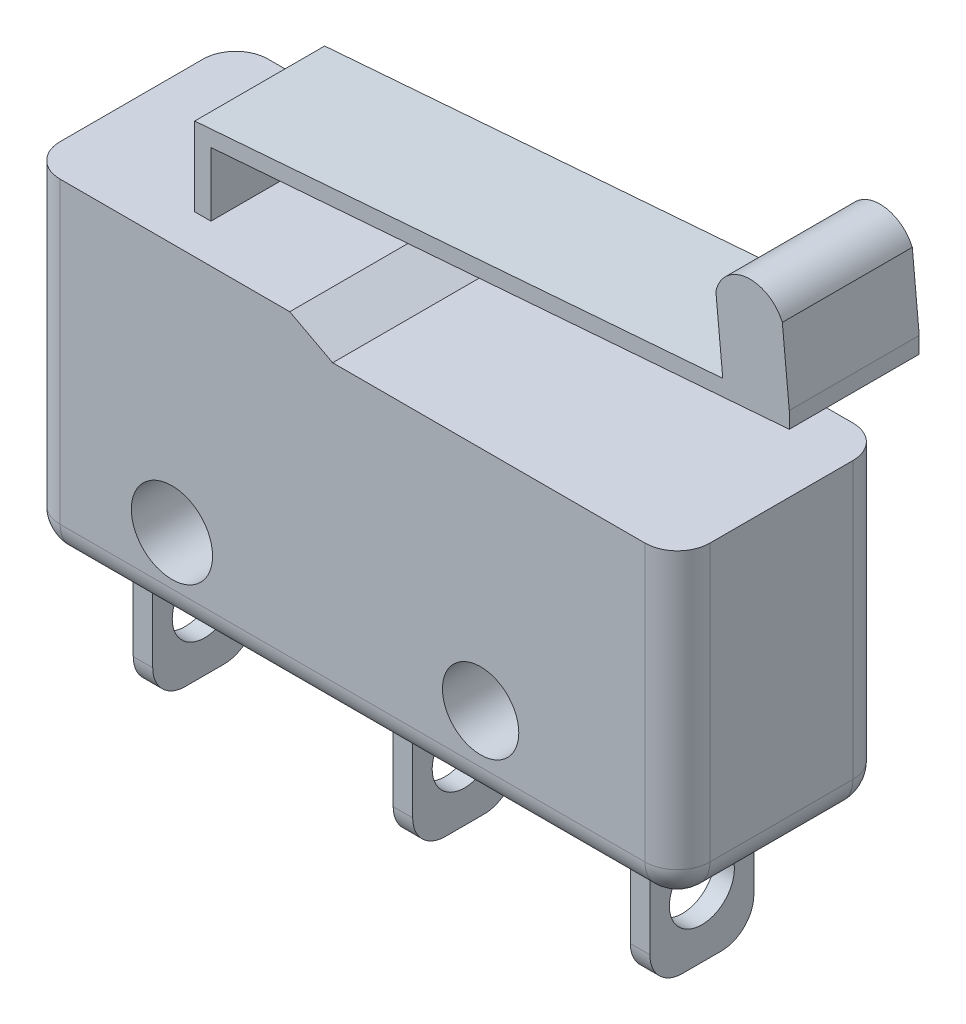
SolidWorks part; units mm, degrees
ref_plane "前视基准面" through (0, 0, 0) normal (0, 0, 1) x (1, 0, 0)
ref_plane "上视基准面" through (0, 0, 0) normal (0, 1, 0) x (1, 0, 0)
ref_plane "右视基准面" through (0, 0, 0) normal (1, 0, 0) x (0, 0, -1)
sketch "草图1" plane through (0, 0, 0) normal (0, 0, 1) x (1, 0, 0)
  line L0 (0, 0) -> (9.5, 0) construction
  line L1 (-4.4408, -2.5) -> (15.5592, -2.5)
  line L2 (15.5592, -2.5) -> (15.5592, 7)
  line L3 (15.5592, 7) -> (4.9467, 7)
  line L4 (4.9467, 7) -> (3.6257, 7.7)
  line L5 (3.6257, 7.7) -> (-4.4408, 7.7)
  line L6 (-4.4408, 7.7) -> (-4.4408, -2.5)
  circle A0 centre (0, 0) radius 1.25
  circle A1 centre (9.5, 0) radius 1.175
  dimension "D2" = 2.5
  dimension "D3" = 2.35
  dimension "D1" = 9.5
  dimension "D4" = 2.5
  dimension "D5" = 20
  dimension "D6" = 9.5
  dimension "D7" = 10.2
extrude "凸台-拉伸1" add sketch "草图1" along normal blind 6.4
sketch "草图3" plane through (0, -2.5, 0) normal (0, -1, 0) x (1, 0, 0)
  line L0 (-4.4408, 6.4) -> (-4.4408, 0) construction
  line L1 (12.5092, 4.8) -> (13.1092, 4.8)
  line L2 (12.5092, 4.8) -> (12.5092, 1.6)
  line L3 (-2.7908, 4.8) -> (-2.1908, 4.8)
  line L4 (-2.7908, 4.8) -> (-2.7908, 1.6)
  line L5 (-2.7908, 1.6) -> (-2.1908, 1.6)
  line L6 (-2.1908, 4.8) -> (-2.1908, 1.6)
  line L7 (5.2092, 4.8) -> (5.8092, 4.8)
  line L8 (5.2092, 4.8) -> (5.2092, 1.6)
  line L9 (5.2092, 1.6) -> (5.8092, 1.6)
  line L10 (5.8092, 4.8) -> (5.8092, 1.6)
  line L11 (12.5092, 1.6) -> (13.1092, 1.6)
  line L12 (13.1092, 4.8) -> (13.1092, 1.6)
  line L13 (-4.4408, 6.4) -> (15.5592, 6.4) construction
  dimension "D1" = 3.2
  dimension "D2" = 0.6
  dimension "D3" = 1.65
  dimension "D4" = 8
  dimension "D5" = 7.3
  dimension "D6" = 1.6
extrude "凸台-拉伸2" add sketch "草图3" along normal blind 4
sketch "草图4" plane through (-2.7908, 0, 0) normal (-1, 0, 0) x (0, 0, 1)
  line L0 (1.6, -2.5) -> (4.8, -6.5) construction
  circle A0 centre (3.2, -4.5) radius 1
extrude "切除-拉伸1" cut sketch "草图4" against normal blind 20
fillet "圆角1" radius 1 6 edges at (12.8092, -6.5, 1.6) (12.8092, -6.5, 4.8) (5.5092, -6.5, 1.6) (5.5092, -6.5, 4.8) (-2.4908, -6.5, 1.6) (-2.4908, -6.5, 4.8)
fillet "圆角2" radius 1 8 edges at (15.5592, -2.5, 3.2) (-4.4408, -2.5, 3.2) (5.5592, -2.5, 0) (5.5592, -2.5, 6.4) (15.5592, 2.25, 0) (15.5592, 2.25, 6.4) (-4.4408, 2.6, 0) (-4.4408, 2.6, 6.4)
ref_plane "基准面1" through (0, 0, 3.2) normal (0, 0, 1) x (1, 0, 0)
sketch "草图5" plane through (0, 0, 3.2) normal (0, 0, 1) x (1, 0, 0)
  line L0 (0, 6.2836) -> (0, 9.6646)
  line L1 (0, 9.6646) -> (17.8, 11.0532)
  line L2 (0, 6.2836) -> (-0.5, 6.2836)
  line L6 (17.8, 11.5555) -> (17.8, 11.0532)
  line L7 (-0.5, 6.2836) -> (-0.5, 10.1191)
  line L8 (17.8, 11.5555) -> (17.586, 13.7957)
  line L9 (17.586, 13.7957) -> (15.5411, 13.6004) construction
  line L10 (15.5411, 13.6004) -> (15.7525, 11.387)
  line L11 (-0.5, 10.1191) -> (15.7525, 11.387)
  arc A0 (15.5411, 13.6004) -> (17.586, 13.7957) centre (16.5944, 13.3747) cw
  dimension "D1" = 0.5
  dimension "D2" = 18.3
extrude "凸台-拉伸3" add sketch "草图5" along normal blind 2 and the other way blind 2
sketch "草图6" plane through (0, 0, 6.4) normal (0, 0, 1) x (1, 0, 0)
  point P0 (0, 0)
  point P1 (9.5, 0)
sketch "草图7" plane through (0, 0, 0) normal (0, 0, -1) x (-1, 0, 0)
  point P0 (-9.5, 0)
  point P1 (0, 0)
